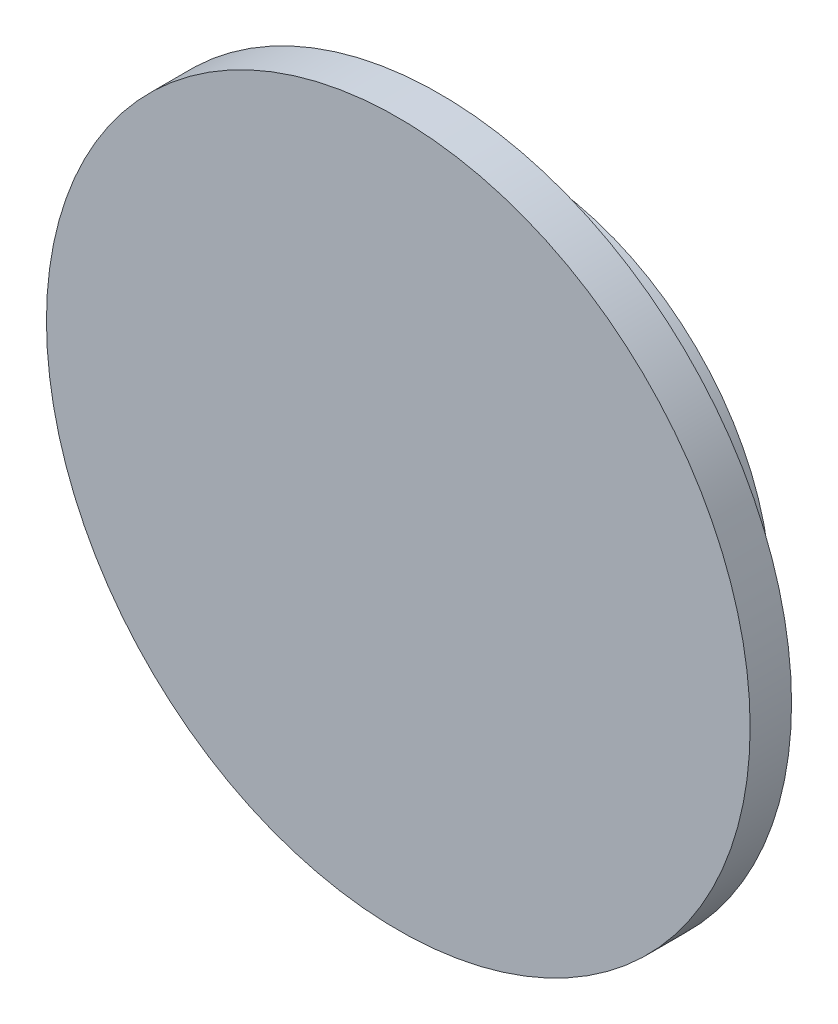
SolidWorks part; units mm, degrees
ref_plane "Plano frontal" through (0, 0, 0) normal (0, 0, 1) x (1, 0, 0)
ref_plane "Plano superior" through (0, 0, 0) normal (0, 1, 0) x (1, 0, 0)
ref_plane "Plano direito" through (0, 0, 0) normal (1, 0, 0) x (0, 0, -1)
sketch "Esboço1" plane through (0, 0, 0) normal (0, 0, 1) x (1, 0, 0)
  circle A0 centre (-200, -240) radius 30 construction
  circle A1 centre (-200, -240) radius 30
extrude "Ressalto-extrusão1" add sketch "Esboço1" against normal blind 10
sketch "Esboço2" plane through (0, 0, 0) normal (0, 0, 1) x (1, 0, 0)
  circle A0 centre (-200, -240) radius 42.5
  circle A1 centre (-200, -240) radius 30 construction
  dimension "D1" = 85
extrude "Ressalto-extrusão2" add sketch "Esboço2" along normal blind 5
